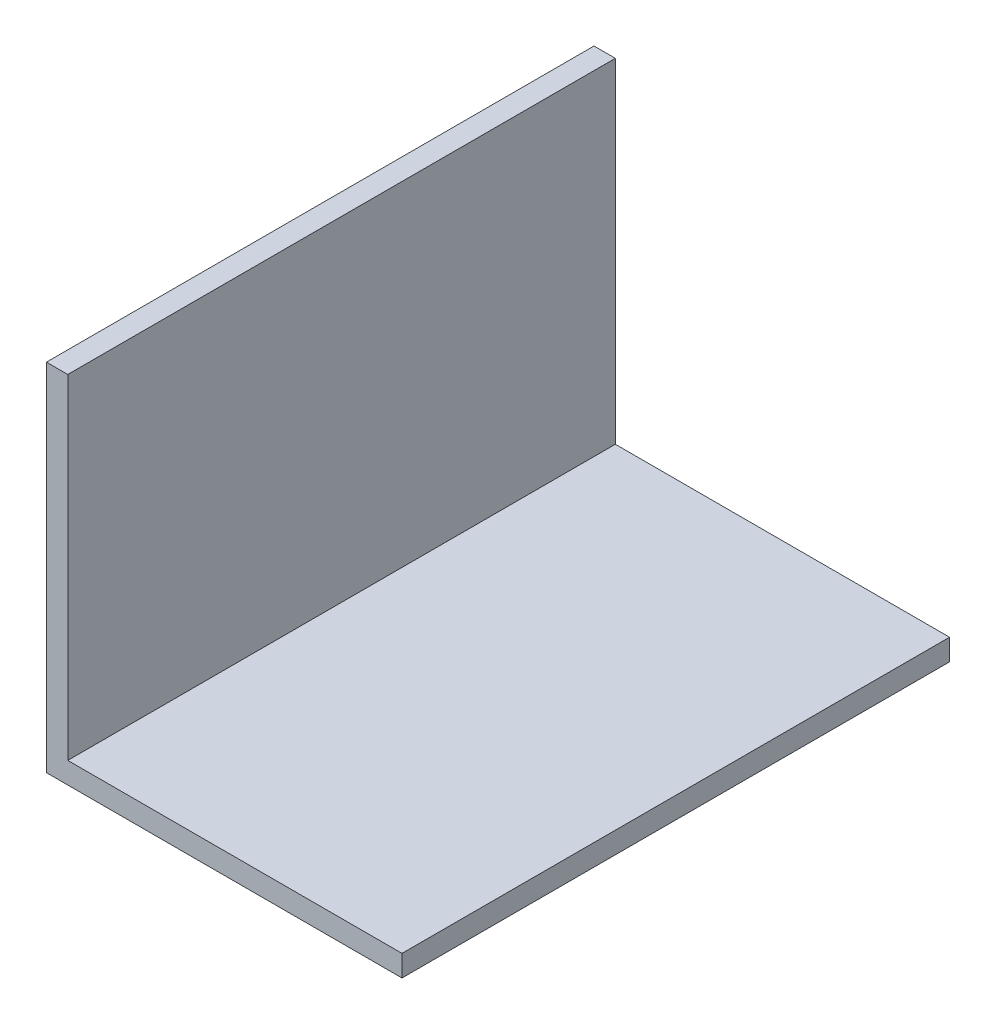
SolidWorks part; units mm, degrees
ref_plane "Front Plane" through (0, 0, 0) normal (0, 0, 1) x (1, 0, 0)
ref_plane "Top Plane" through (0, 0, 0) normal (0, 1, 0) x (1, 0, 0)
ref_plane "Right Plane" through (0, 0, 0) normal (1, 0, 0) x (0, 0, -1)
sketch "Sketch1" plane through (0, 0, 0) normal (0, 0, 1) x (1, 0, 0)
  line L0 (0, 0) -> (0, 25)
  line L2 (0, 25) -> (1.5, 25)
  line L3 (1.5, 25) -> (1.5, 1.5)
  line L4 (1.5, 1.5) -> (25, 1.5)
  line L5 (25, 1.5) -> (25, 0)
  line L7 (25, 0) -> (0, 0)
  dimension "D1" = 25
  dimension "D2" = 1.5
extrude "Boss-Extrude1" add sketch "Sketch1" along normal blind 38.5
